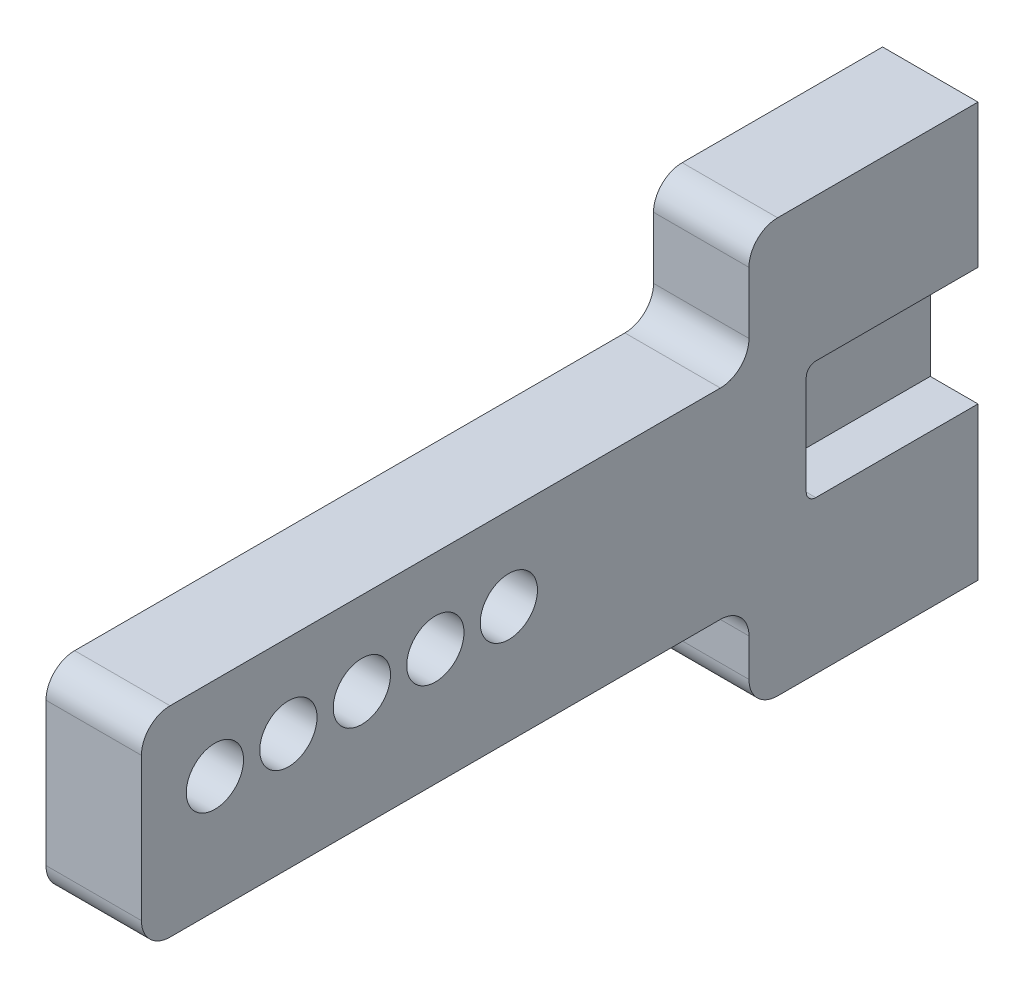
SolidWorks part; units mm, degrees
ref_plane "Alzado" through (0, 0, 0) normal (0, 0, 1) x (1, 0, 0)
ref_plane "Planta" through (0, 0, 0) normal (0, 1, 0) x (1, 0, 0)
ref_plane "Vista lateral" through (0, 0, 0) normal (1, 0, 0) x (0, 0, -1)
sketch "Croquis1" plane through (0, 0, 0) normal (1, 0, 0) x (0, 0, -1)
  line L0 (0, -10.2165) -> (0, 27.3947)
  line L1 (0, 27.3947) -> (-24, 27.3947)
  line L2 (-24, 27.3947) -> (-24, 14.9424)
  line L3 (-24, 14.9424) -> (-87.6638, 14.9424)
  line L4 (-87.6638, 14.9424) -> (-87.6638, -6.0576)
  line L5 (-87.6638, -6.0576) -> (-24, -6.0576)
  line L6 (-24, -6.0576) -> (-24, -16.0028)
  line L7 (-24, -16.0028) -> (0, -16.0028)
  line L8 (0, -16.0028) -> (0, -10.2165)
  dimension "D1" = 24
  dimension "D2" = 24
  dimension "D3" = 21
extrude "Saliente-Extruir1" add sketch "Croquis1" along normal blind 10
sketch "Croquis2" plane through (10, 0, 0) normal (1, 0, 0) x (0, 0, -1)
  line L0 (0, 0) -> (-18, 0)
  line L1 (-18, 0) -> (-18, 12.3947)
  line L2 (-18, 12.3947) -> (0, 12.3947)
  line L3 (0, -16.0028) -> (0, 27.3947) construction
  line L4 (0, 12.3947) -> (0, 0)
  line L5 (0, 27.3947) -> (-24, 27.3947) construction
  dimension "D1" = 15
  dimension "D2" = 18
extrude "Cortar-Extruir1" cut sketch "Croquis2" against normal blind 5
fillet "Redondeo1" radius 3 2 edges at (5, -6.0576, 24) (5, 14.9424, 24)
fillet "Redondeo2" radius 3 4 edges at (5, -16.0028, 24) (5, 27.3947, 24) (5, -6.0576, 87.6638) (5, 14.9424, 87.6638)
fillet "Redondeo3" radius 1 2 edges at (7.5, 0, 18) (7.5, 12.3947, 18)
sketch "Croquis3" plane through (10, 0, 0) normal (1, 0, 0) x (0, 0, -1)
  line L0 (0, 6.1974) -> (-100.3043, 6.1974) construction
  line L1 (0, 0) -> (0, 12.3947) construction
  line L2 (-87.6638, 11.9424) -> (-87.6638, -3.0576) construction
  circle A0 centre (-79.9638, 6.1974) radius 3
  circle A1 centre (-72.2638, 6.1974) radius 3
  circle A2 centre (-64.5638, 6.1974) radius 3
  circle A3 centre (-56.8638, 6.1974) radius 3
  circle A4 centre (-49.1638, 6.1974) radius 3
  dimension "D2" = 7.7
  dimension "D3" = 7.7
  dimension "D4" = 7.7
  dimension "D5" = 7.7
  dimension "D6" = 6
  dimension "D7" = 6
  dimension "D8" = 6
  dimension "D9" = 6
  dimension "D10" = 6
  dimension "D1" = 7.7
extrude "Cortar-Extruir2" cut sketch "Croquis3" against normal blind 15
